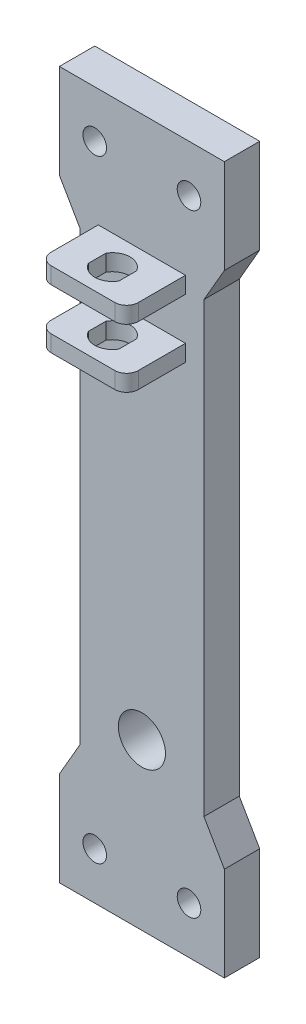
SolidWorks part; units mm, degrees
ref_plane "Front Plane" through (0, 0, 0) normal (0, 0, 1) x (1, 0, 0)
ref_plane "Top Plane" through (0, 0, 0) normal (0, 1, 0) x (1, 0, 0)
ref_plane "Right Plane" through (0, 0, 0) normal (1, 0, 0) x (0, 0, -1)
sketch "Sketch2" plane through (0, 0, 0) normal (0, 0, 1) x (1, 0, 0)
  line L0 (-35, 110) -> (-26.3397, 95)
  line L1 (-35, 150) -> (35, 150)
  line L2 (-35, 150) -> (-35, 110)
  line L3 (-35, -150) -> (35, -150)
  line L4 (35, 150) -> (35, 110)
  line L5 (-35, 150) -> (35, -150) construction
  line L6 (-35, -150) -> (35, 150) construction
  line L7 (-26.3397, 95) -> (-26.3397, -95)
  line L8 (-26.3397, -95) -> (-35, -110)
  line L9 (0, 158.9917) -> (0, -175.3985) construction
  line L10 (26.3397, -95) -> (35, -110)
  line L11 (26.3397, 95) -> (26.3397, -95)
  line L12 (35, 110) -> (26.3397, 95)
  line L13 (-35, -110) -> (-35, -150)
  line L14 (35, -110) -> (35, -150)
  point P0 (0, 0)
  dimension "D1" = 70
  dimension "D2" = 300
  dimension "D3" = 40
  dimension "D4" = 40
  dimension "D5" = 30
  dimension "D6" = 190
extrude "Boss-Extrude1" add sketch "Sketch2" along normal blind 15
sketch "Sketch3" plane through (0, 0, 15) normal (0, 0, 1) x (1, 0, 0)
  line L0 (0, 174.5944) -> (0, -230.8171) construction
  line L1 (35, 150) -> (-35, 150) construction
  line L2 (-39.0944, 0) -> (65.572, 0) construction
  circle A0 centre (-20, 130) radius 5
  circle A1 centre (20, 130) radius 5
  circle A2 centre (20, -130) radius 5
  circle A3 centre (-20, -130) radius 5
  dimension "D1" = 10
  dimension "D2" = 10
  dimension "D5" = 20
  dimension "D6" = 20
  dimension "D3" = 20
  dimension "D4" = 20
extrude "Cut-Extrude1" cut sketch "Sketch3" against normal through all
sketch "Sketch4" plane through (0, 0, 15) normal (0, 0, 1) x (1, 0, 0)
  line L0 (-35, -150) -> (35, -150) construction
  circle A0 centre (0, -80) radius 10
  dimension "D1" = 20
  dimension "D2" = 70
extrude "Cut-Extrude2" cut sketch "Sketch4" against normal through all
sketch "Sketch6" plane through (0, 0, 15) normal (0, 0, 1) x (1, 0, 0)
  line L0 (0, 175.7812) -> (0, -42.4076) construction
  line L1 (35, 150) -> (-35, 150) construction
  line L2 (-18.5, 100) -> (18.5, 100)
  line L3 (-18.5, 100) -> (-18.5, 93)
  line L4 (-18.5, 93) -> (18.5, 93)
  line L5 (18.5, 100) -> (18.5, 93)
  line L6 (-18.5, 100) -> (18.5, 93) construction
  line L7 (-18.5, 93) -> (18.5, 100) construction
  line L9 (-18.5, 75) -> (18.5, 75)
  line L10 (-18.5, 75) -> (-18.5, 68)
  line L11 (-18.5, 68) -> (18.5, 68)
  line L12 (18.5, 75) -> (18.5, 68)
  line L13 (-18.5, 75) -> (18.5, 68) construction
  line L14 (-18.5, 68) -> (18.5, 75) construction
  point P3 (0, 96.5)
  point P10 (0, 71.5)
  point P15 (0, 0)
  point P16 (0, 0)
  dimension "D1" = 37
  dimension "D2" = 7
  dimension "D3" = 50
  dimension "D4" = 7
  dimension "D5" = 25
extrude "Boss-Extrude2" add sketch "Sketch6" along normal blind 25
sketch "Sketch7" plane through (0, 68, 0) normal (0, -1, 0) x (1, 0, 0)
  line L0 (-18.5, 15) -> (18.5, 15) construction
  line L1 (-6.5, 31.2417) -> (-6.5, 23.7583)
  line L2 (0, 39.2461) -> (0, 18.5199) construction
  line L3 (6.5, 31.2417) -> (6.5, 23.7583)
  arc A0 (-6.5, 23.7583) -> (6.5, 23.7583) centre (0, 27.5) ccw
  arc A1 (6.5, 31.2417) -> (-6.5, 31.2417) centre (0, 27.5) ccw
  dimension "D1" = 15
  dimension "D2" = 12.5
  dimension "D3" = 6.5
extrude "Cut-Extrude3" cut sketch "Sketch7" against normal blind 32
fillet "Fillet3" radius 5 4 edges at (18.5, 96.5, 40) (18.5, 71.5, 40) (-18.5, 96.5, 40) (-18.5, 71.5, 40)
